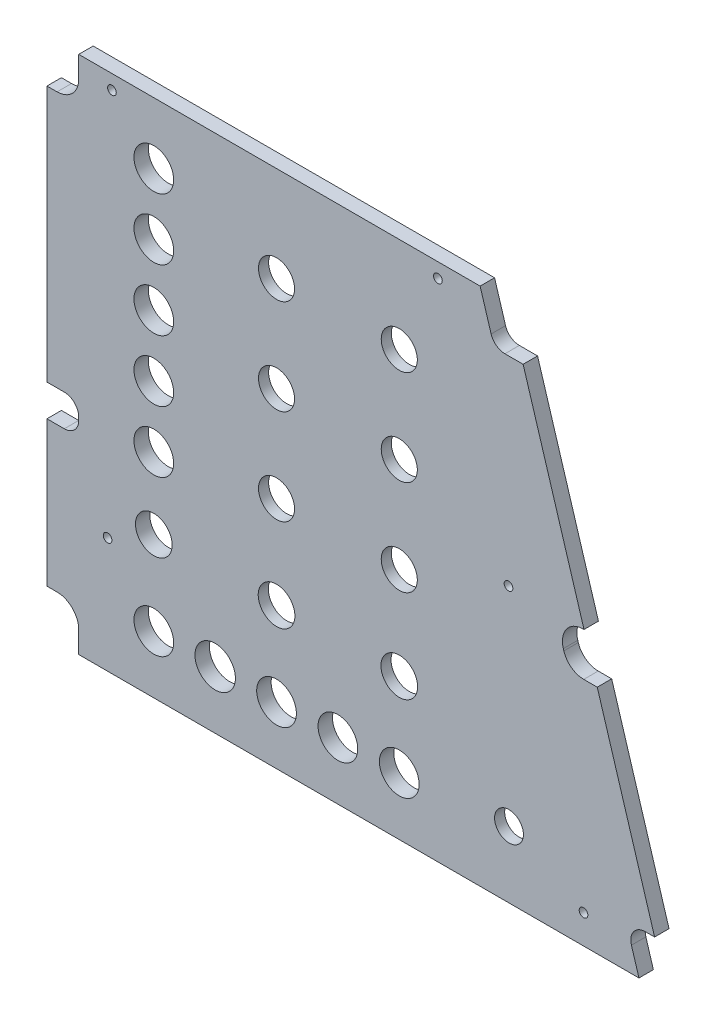
SolidWorks part; units mm, degrees
ref_plane "Front Plane" through (0, 0, 0) normal (0, 0, 1) x (1, 0, 0)
ref_plane "Top Plane" through (0, 0, 0) normal (0, 1, 0) x (1, 0, 0)
ref_plane "Right Plane" through (0, 0, 0) normal (1, 0, 0) x (0, 0, -1)
sketch "Sketch1" plane through (0, 0, 0) normal (0, 0, 1) x (1, 0, 0)
  line L4 (26.6105, 114.5078) -> (26.6105, -23.6594) construction
  line L9 (75.8605, 85.6434) -> (-63.1395, 85.6434) construction
  line L10 (-63.1395, -94.3566) -> (130.8605, -94.3566) construction
  line L37 (-74.1395, 85.6434) -> (85.8605, 85.6434)
  line L41 (85.8605, 85.6434) -> (140.8605, -94.3566)
  line L42 (140.8605, -94.3566) -> (-74.1395, -94.3566)
  line L44 (-74.1395, -94.3566) -> (-74.1395, 85.6434)
  circle A0 centre (-37.1395, 64.3934) radius 6.875
  circle A1 centre (-37.1395, 43.1434) radius 6.875
  circle A2 centre (-37.1395, 21.8934) radius 6.875
  circle A3 centre (-37.1395, 0.6434) radius 6.875
  circle A4 centre (-37.1395, -20.6066) radius 6.875
  circle A5 centre (5.3605, 52.6434) radius 6.25
  circle A7 centre (5.3605, 19.6434) radius 6.25
  circle A8 centre (5.3605, -13.3566) radius 6.25
  circle A11 centre (47.8605, -13.3566) radius 6.25
  circle A12 centre (47.8605, 19.6434) radius 6.25
  circle A14 centre (47.8605, 52.6434) radius 6.25
  circle A15 centre (-37.1395, -45.3566) radius 6.35
  circle A16 centre (5.3605, -45.3566) radius 6.35
  circle A17 centre (47.8605, -45.3566) radius 6.35
  circle A18 centre (-37.1395, -74.3566) radius 6.875
  circle A19 centre (-15.8895, -74.3566) radius 7
  circle A20 centre (5.3605, -74.3566) radius 6.875
  circle A21 centre (26.6105, -74.3566) radius 6.875
  circle A22 centre (47.8605, -74.3566) radius 6.875
  circle A23 centre (85.8605, -71.3566) radius 5
  circle A24 centre (-51.6395, 80.6434) radius 1.5
  circle A25 centre (61.2473, 80.6434) radius 1.5
  circle A26 centre (85.6917, 0.6434) radius 1.5
  circle A27 centre (111.6639, -84.3566) radius 1.5
  circle A28 centre (-53.1395, -54.3566) radius 1.5
  dimension "D32" = 12.5
  dimension "D12" = 12.5
  dimension "D33" = 12.5
  dimension "D34" = 12.7
  dimension "D35" = 12.7
  dimension "D36" = 12.7
  dimension "D45" = 3
  dimension "D46" = 3
  dimension "D50" = 3
  dimension "D53" = 3
  dimension "D57" = 3
  dimension "D58" = 13.75
  dimension "D59" = 13.75
  dimension "D60" = 13.75
  dimension "D61" = 13.75
  dimension "D62" = 13.75
  dimension "D63" = 13.75
  dimension "D64" = 14
  dimension "D65" = 13.75
  dimension "D66" = 13.75
  dimension "D67" = 13.75
  dimension "D68" = 10
  dimension "D1" = 37
  dimension "D2" = 37
  dimension "D3" = 37
  dimension "D4" = 37
  dimension "D5" = 37
  dimension "D6" = 37
  dimension "D7" = 42.5
  dimension "D8" = 42.5
  dimension "D9" = 42.5
  dimension "D10" = 42.5
  dimension "D11" = 42.5
  dimension "D13" = 42.5
  dimension "D14" = 5
  dimension "D15" = 37
  dimension "D16" = 21.25
  dimension "D17" = 21.25
  dimension "D18" = 21.25
  dimension "D19" = 21.25
  dimension "D20" = 20
  dimension "D21" = 20
  dimension "D22" = 20
  dimension "D23" = 20
  dimension "D24" = 20
  dimension "D25" = 23
  dimension "D26" = 215
  dimension "D27" = 21.25
  dimension "D28" = 21.25
  dimension "D29" = 21.25
  dimension "D30" = 21.25
  dimension "D31" = 21.25
  dimension "D37" = 33
  dimension "D38" = 33
  dimension "D39" = 33
  dimension "D40" = 32
  dimension "D41" = 32
  dimension "D42" = 160
  dimension "D43" = 55
  dimension "D44" = 22.5
  dimension "D47" = 5
  dimension "D48" = 25
  dimension "D49" = 25
  dimension "D51" = 95
  dimension "D52" = 25
  dimension "D54" = 10
  dimension "D55" = 21
  dimension "D56" = 40
  dimension "D69" = 0
  dimension "D70" = 0
extrude "Boss-Extrude1" add sketch "Sketch1" along normal blind 5
sketch "Sketch6" plane through (0, 0, 5) normal (0, 0, 1) x (1, 0, 0)
  circle A0 centre (5.3605, 52.6434) radius 10
  circle A1 centre (47.8605, 52.6434) radius 10
  circle A8 centre (47.8605, -45.3566) radius 10
  circle A9 centre (47.8605, -13.3566) radius 10
  circle A10 centre (47.8605, 19.6434) radius 10
  circle A13 centre (5.3605, 19.6434) radius 10
  circle A14 centre (5.3605, -13.3566) radius 10
  circle A15 centre (5.3605, -45.3566) radius 10
  circle A17 centre (85.8605, -71.3566) radius 10
  circle A23 centre (5.3605, 52.6434) radius 6.25 construction
  circle A25 centre (5.3605, 19.6434) radius 6.25 construction
  circle A26 centre (5.3605, -13.3566) radius 6.25 construction
  circle A27 centre (5.3605, -45.3566) radius 6.35 construction
  circle A28 centre (47.8605, -45.3566) radius 6.35 construction
  circle A29 centre (47.8605, -13.3566) radius 6.25 construction
  circle A30 centre (47.8605, 19.6434) radius 6.25 construction
  circle A32 centre (47.8605, 52.6434) radius 6.25 construction
  circle A37 centre (85.8605, -71.3566) radius 5 construction
  dimension "D1" = 20
  dimension "D3" = 20
  dimension "D4" = 20
  dimension "D5" = 20
  dimension "D6" = 20
  dimension "D7" = 20
  dimension "D8" = 20
  dimension "D10" = 20
  dimension "D11" = 20
  dimension "D19" = 0
  dimension "D20" = 0
  dimension "D21" = 0
  dimension "D22" = 0
  dimension "D23" = 0
  dimension "D24" = 0
  dimension "D26" = 0
  dimension "D17" = 0
  dimension "D31" = 0
sketch "Sketch3" plane through (0, 0, 0) normal (0, 0, 1) x (1, 0, 0)
  line L3 (-74.1395, 70.6434) -> (-70.6395, 70.6434)
  line L4 (-63.1395, 85.6434) -> (-63.1395, 78.1434)
  line L5 (136.2772, -79.3566) -> (133.0332, -79.3566)
  line L11 (75.8605, 85.6434) -> (79.6681, 73.1823)
  line L14 (-74.1395, -79.3566) -> (-70.6395, -79.3566)
  line L15 (-63.1395, -94.3566) -> (-63.1395, -86.8566)
  line L16 (-74.1395, -18.1466) -> (-68.1395, -18.1466)
  line L21 (-74.1395, -18.1466) -> (-74.1395, -29.1466)
  line L22 (-74.1395, -29.1466) -> (-68.1395, -29.1466)
  line L23 (-63.1395, -23.1466) -> (-63.1395, -24.1466)
  line L40 (84.4498, 69.6434) -> (90.7494, 69.6434)
  line L53 (-74.1395, -79.3566) -> (-74.1395, -94.3566)
  line L55 (-74.1395, -94.3566) -> (-63.1395, -94.3566)
  line L56 (-63.1395, 85.6434) -> (-74.1395, 85.6434)
  line L66 (-74.1395, 85.6434) -> (-74.1395, 70.6434)
  line L69 (-74.1395, -94.3566) -> (140.8605, -94.3566) construction
  line L70 (-74.1395, -94.3566) -> (140.8605, -94.3566) construction
  line L71 (85.8605, 85.6434) -> (-74.1395, 85.6434) construction
  line L74 (75.8605, 85.6434) -> (85.8605, 85.6434)
  line L75 (85.8605, 85.6434) -> (90.7494, 69.6434)
  line L76 (71.7254, 99.1765) -> (133.5603, -103.1923) construction
  line L77 (128.2514, -85.8177) -> (130.8605, -94.3566)
  line L78 (84.4498, 69.6434) -> (90.7494, 69.6434) construction
  line L82 (136.2772, -79.3566) -> (140.8605, -94.3566)
  line L83 (130.8605, -94.3566) -> (140.8605, -94.3566)
  line L86 (111.8327, 0.6434) -> (116.4161, -14.3566)
  line L87 (111.8327, 0.6434) -> (111.5614, 0.6434)
  line L88 (116.4161, -14.3566) -> (111.7447, -14.3566)
  line L89 (104.859, -9.2606) -> (104.6756, -8.6606)
  line L91 (140.8605, -94.3566) -> (85.8605, 85.6434) construction
  line L92 (85.8605, 85.6434) -> (-74.1395, 85.6434) construction
  line L93 (-74.1395, 85.6434) -> (-74.1395, -94.3566) construction
  arc A1 (-70.6395, -79.3566) -> (-63.1395, -86.8566) centre (-70.6395, -86.8566) cw
  arc A3 (-63.1395, 78.1434) -> (-70.6395, 70.6434) centre (-70.6395, 78.1434) cw
  arc A4 (-63.1395, -23.1466) -> (-68.1395, -18.1466) centre (-68.1395, -23.1466) ccw
  arc A5 (-63.1395, -24.1466) -> (-68.1395, -29.1466) centre (-68.1395, -24.1466) cw
  arc A12 (79.6681, 73.1823) -> (84.4498, 69.6434) centre (84.4498, 74.6434) ccw
  arc A13 (128.2514, -85.8177) -> (133.0332, -79.3566) centre (133.0332, -84.3566) cw
  arc A14 (111.7447, -14.3566) -> (104.859, -9.2606) centre (111.7447, -7.1566) cw
  arc A15 (104.6756, -8.6606) -> (111.5614, 0.6434) centre (111.5614, -6.5566) cw
  point P34 (-63.1395, -79.3566)
  point P35 (80.7494, 69.6434)
  point P40 (-63.1395, 70.6434)
  point P43 (-63.1395, -18.1466)
  point P50 (126.2772, -79.3566)
  point P55 (106.4161, -14.3566)
  point P59 (101.8327, 0.6434)
  dimension "D11" = 10
  dimension "D12" = 5
  dimension "D13" = 15
  dimension "D18" = 10
  dimension "D17" = 80
  dimension "D19" = 5
  dimension "D22" = 5
  dimension "D14" = 7.2
  dimension "D1" = 11
  dimension "D2" = 15
  dimension "D3" = 0
  dimension "D4" = 0
  dimension "D5" = 10
  dimension "D6" = 0
  dimension "D7" = 15
  dimension "D8" = 11
  dimension "D9" = 0
  dimension "D10" = 0
  dimension "D15" = 0
  dimension "D16" = 0
  dimension "D20" = 0
  dimension "D21" = 103.79
  dimension "D23" = 0
  dimension "D24" = 11
  dimension "D25" = 0
extrude "Cut-Extrude1" cut sketch "Sketch6" along normal blind 1.5 from offset 5 offset against normal yes
extrude "Cut-Extrude2" cut sketch "Sketch3" along normal blind 5
